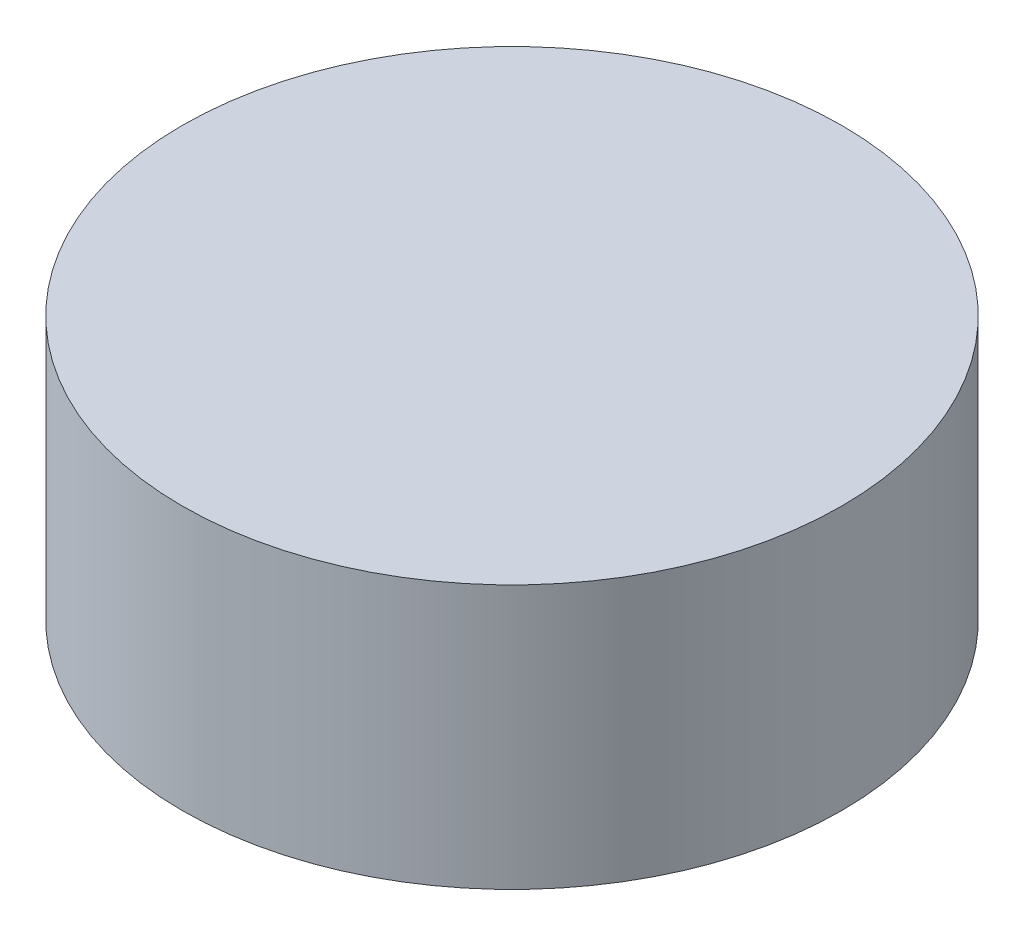
SolidWorks part; units mm, degrees
ref_plane "Front Plane" through (0, 0, 0) normal (0, 0, 1) x (1, 0, 0)
ref_plane "Top Plane" through (0, 0, 0) normal (0, 1, 0) x (1, 0, 0)
ref_plane "Right Plane" through (0, 0, 0) normal (1, 0, 0) x (0, 0, -1)
sketch "Sketch6" plane through (0, 0, 0) normal (0, 1, 0) x (1, 0, 0)
  circle A0 centre (0, 0) radius 12.7
  dimension "D1" = 25.4
extrude "Extrude5" add sketch "Sketch6" against normal blind 10.16
sketch "Sketch7" plane through (0, 0, 0) normal (0, 1, 0) x (1, 0, 0)
  circle A0 centre (0, 0) radius 10.2777
